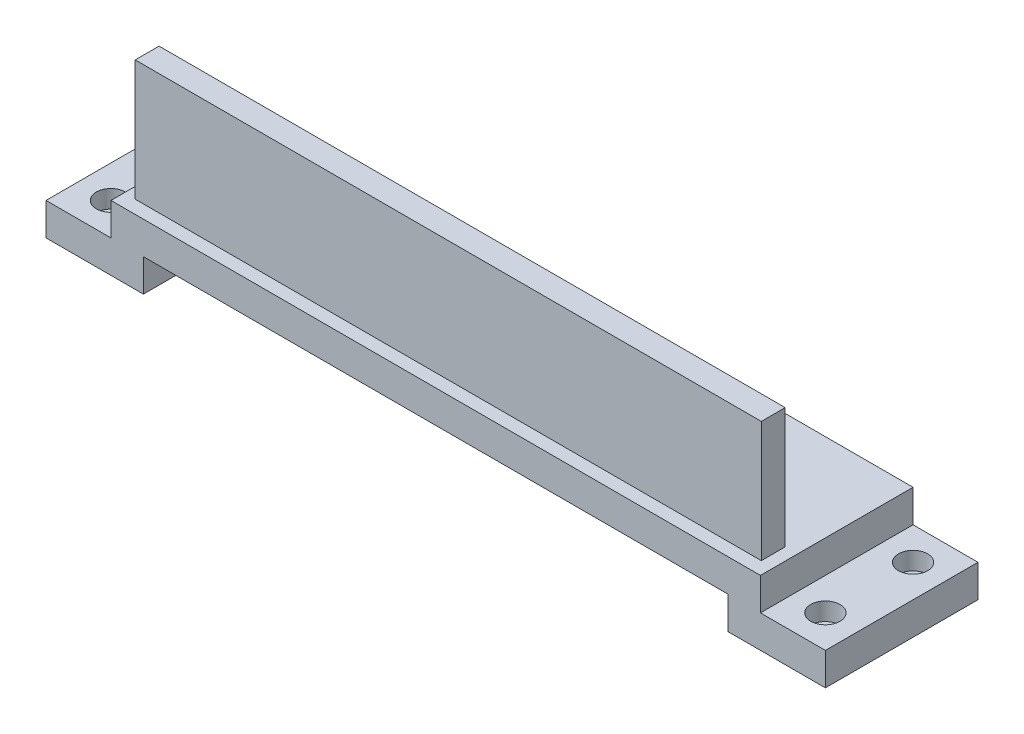
SolidWorks part; units mm, degrees
ref_plane "前视基准面" through (0, 0, 0) normal (0, 0, 1) x (1, 0, 0)
ref_plane "上视基准面" through (0, 0, 0) normal (0, 1, 0) x (1, 0, 0)
ref_plane "右视基准面" through (0, 0, 0) normal (1, 0, 0) x (0, 0, -1)
other "Configuration Table"
ref_plane "基准面1" through (0, -20, 0) normal (0, -1, 0) x (1, 0, 0)
sketch "草图1" plane through (0, -20, 0) normal (0, -1, 0) x (1, 0, 0)
  line L0 (240, 47) -> (-240, 47)
  line L1 (-240, 47) -> (-240, -47)
  line L2 (-240, -47) -> (240, -47)
  line L3 (240, -47) -> (240, 47)
extrude "凸台-拉伸1" add sketch "草图1" against normal blind 40
sketch "草图2" plane through (0, 0, -47) normal (0, 0, -1) x (-1, 0, 0)
  line L0 (200, 20) -> (200, 0)
  line L1 (200, 0) -> (240, 0)
  line L2 (240, 0) -> (240, 20)
  line L3 (240, 20) -> (200, 20)
extrude "切除-拉伸1" cut sketch "草图2" against normal through all
sketch "草图3" plane through (0, 0, -47) normal (0, 0, -1) x (-1, 0, 0)
  line L0 (-180, -20) -> (180, -20)
  line L1 (180, -20) -> (180, 0)
  line L2 (180, 0) -> (-180, 0)
  line L3 (-180, 0) -> (-180, -20)
extrude "切除-拉伸2" cut sketch "草图3" against normal through all
sketch "草图4" plane through (0, 0, -47) normal (0, 0, -1) x (-1, 0, 0)
  line L0 (-240, 0) -> (-200, 0)
  line L1 (-200, 0) -> (-200, 20)
  line L2 (-200, 20) -> (-240, 20)
  line L3 (-240, 20) -> (-240, 0)
extrude "切除-拉伸3" cut sketch "草图4" against normal through all
hole_wizard "M10 六角头螺栓的柱形沉头孔1" positions "草图8" profile "草图7" counterbore size "M10" standard "ANSI Metric"
sketch "草图8" plane through (0, 0, 0) normal (0, 1, 0) x (1, 0, 0)
  point P0 (220, -27)
  point P1 (220, 27)
  point P2 (-220, -27)
  point P3 (-220, 27)
sketch "草图7" plane through (220, 0, 27) normal (1, 0, 0) x (0, 0, 1)
  line L0 (0, 0) -> (0, 20)
  line L1 (0, 20) -> (5.5, 20)
  line L3 (5.5, 20) -> (5.5, 11)
  line L4 (5.5, 11) -> (9, 11)
  line L5 (9, 11) -> (9, 0)
  line L7 (9, 0) -> (0, 0)
  line L11 (0, -6.35) -> (0, 107.95) construction
  dimension "通孔孔直径" = 11
  dimension "通孔孔深度" = 20
  dimension "柱形沉头孔直径" = 18
  dimension "柱形沉头孔深度" = 11
ref_plane "基准面2" through (-200, 0, 0) normal (-1, 0, 0) x (0, 0, 1)
sketch "草图9" plane through (0, 20, 0) normal (0, 1, 0) x (1, 0, 0)
  line L1 (-193.1899, -38.87) -> (192.4163, -38.87)
  line L2 (-193.1899, -38.87) -> (-193.1899, -24.1729)
  line L3 (-193.1899, -24.1729) -> (192.4163, -24.1729)
  line L4 (192.4163, -38.87) -> (192.4163, -24.1729)
extrude "凸台-拉伸2" add sketch "草图9" along normal blind 74.29 contours L2 L1 L4 L3
